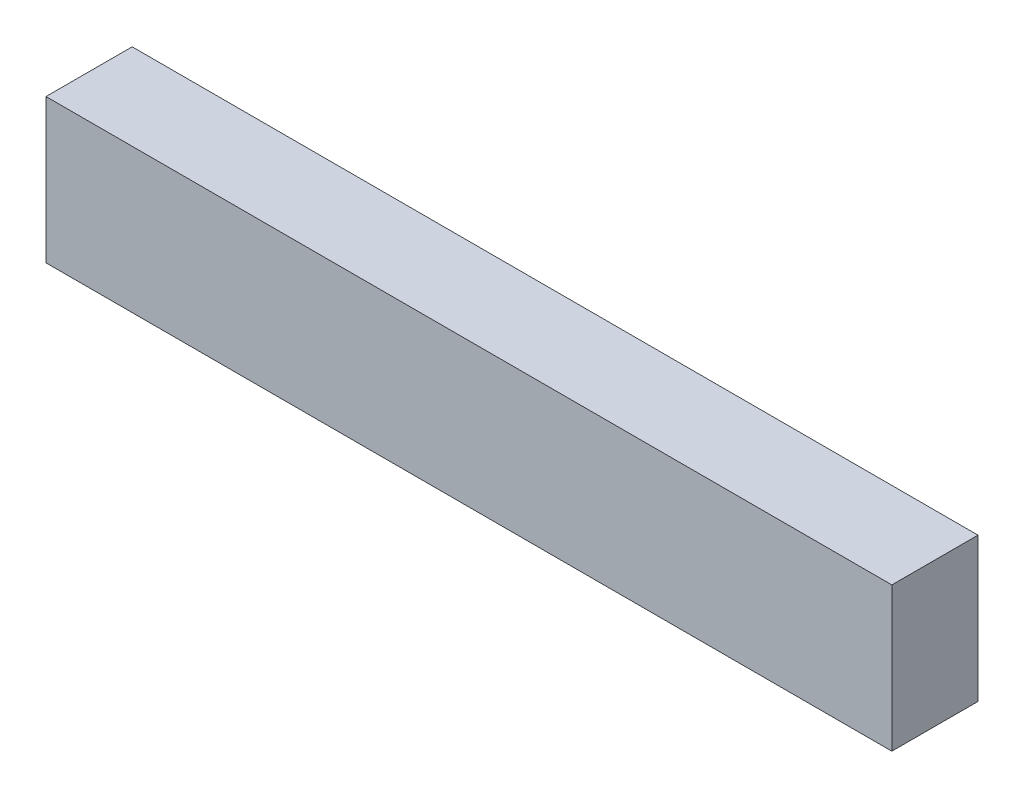
SolidWorks part; units mm, degrees
ref_plane "Front Plane" through (0, 0, 0) normal (0, 0, 1) x (1, 0, 0)
ref_plane "Top Plane" through (0, 0, 0) normal (0, 1, 0) x (1, 0, 0)
ref_plane "Right Plane" through (0, 0, 0) normal (1, 0, 0) x (0, 0, -1)
sketch "Sketch1" plane through (0, 0, 0) normal (0, 0, 1) x (1, 0, 0)
  line L0 (-79.2368, -65.25) -> (-7.6555, -65.25) construction
  line L1 (-79.0368, -65.45) -> (-7.8555, -65.45)
  line L2 (-79.0368, -65.45) -> (-79.0368, -77.5714)
  line L3 (-79.0368, -77.5714) -> (-7.8555, -77.5714)
  line L4 (-7.8555, -65.45) -> (-7.8555, -77.5714)
  line L5 (-7.6555, -65.25) -> (-7.6555, -77.7714) construction
  line L6 (-79.2368, -77.7714) -> (-7.6555, -77.7714) construction
  line L7 (-79.2368, -65.25) -> (-79.2368, -77.7714) construction
  dimension "D1" = 0.2
  dimension "D2" = 0.2
  dimension "D3" = 0.2
  dimension "D4" = 0.2
extrude "Boss-Extrude1" add sketch "Sketch1" along normal blind 7.25
shell "Shell1" thickness 0.5
equation "\"D2@Sketch1\"=\"D1@Sketch1\""
equation "\"D3@Sketch1\"=\"D1@Sketch1\""
equation "\"D4@Sketch1\"=\"D1@Sketch1\""
